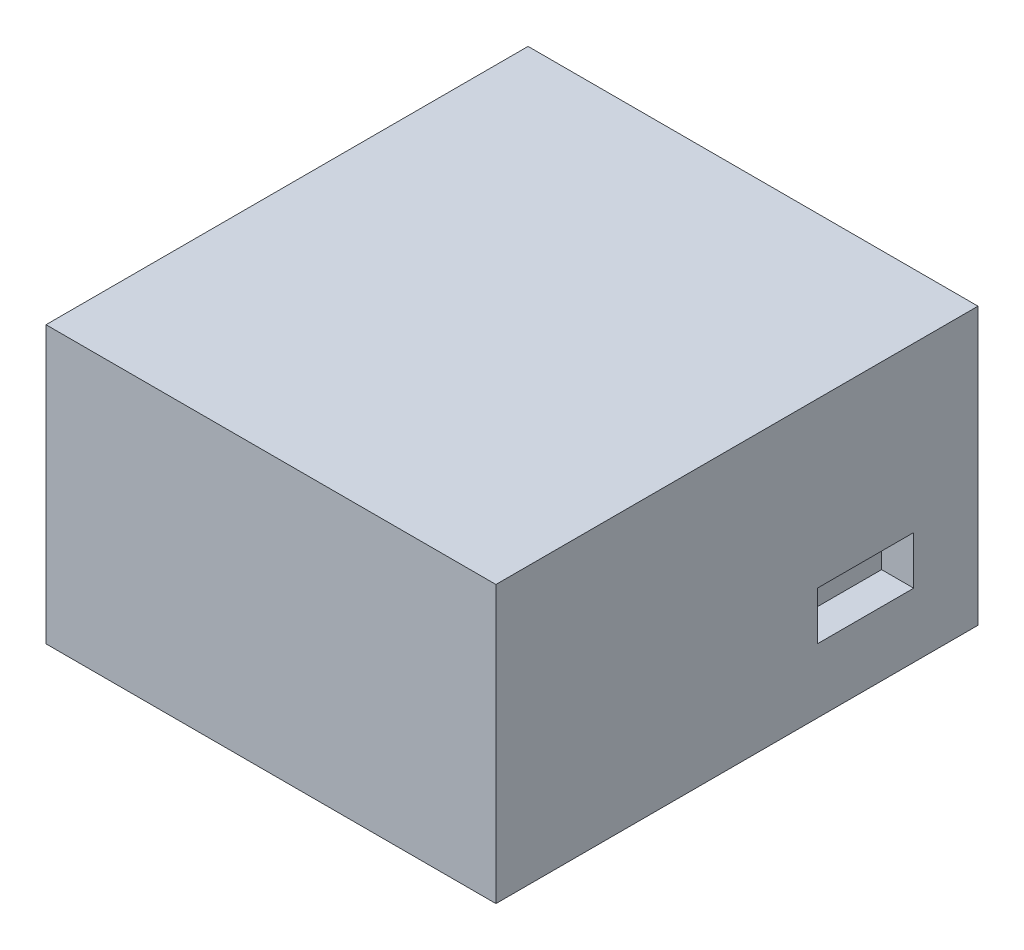
SolidWorks part; units mm, degrees
ref_plane "Alzado" through (0, 0, 0) normal (0, 0, 1) x (1, 0, 0)
ref_plane "Planta" through (0, 0, 0) normal (0, 1, 0) x (1, 0, 0)
ref_plane "Vista lateral" through (0, 0, 0) normal (1, 0, 0) x (0, 0, -1)
sketch "Croquis1" plane through (0, 0, 0) normal (0, 1, 0) x (1, 0, 0)
  line L1 (-70, -75) -> (70, -75)
  line L2 (-70, -75) -> (-70, 75)
  line L3 (-70, 75) -> (70, 75)
  line L4 (70, -75) -> (70, 75)
  line L5 (-70, -75) -> (70, 75) construction
  line L6 (-70, 75) -> (70, -75) construction
  point P0 (0, 0)
  dimension "D1" = 140
  dimension "D2" = 150
extrude "Saliente-Extruir1" add sketch "Croquis1" along normal blind 86
sketch "Croquis3" plane through (70, 0, 0) normal (1, 0, 0) x (0, 0, -1)
  line L0 (75, 86) -> (75, 0) construction
  line L1 (25, 35) -> (55, 35)
  line L2 (25, 35) -> (25, 20)
  line L3 (25, 20) -> (55, 20)
  line L4 (55, 35) -> (55, 20)
  line L5 (25, 35) -> (55, 20) construction
  line L6 (25, 20) -> (55, 35) construction
  line L7 (-75, 0) -> (75, 0) construction
  point P0 (40, 27.5)
  dimension "D1" = 30
  dimension "D2" = 15
  dimension "D3" = 20
  dimension "D4" = 20
extrude "Cortar-Extruir1" cut sketch "Croquis3" against normal blind 10
